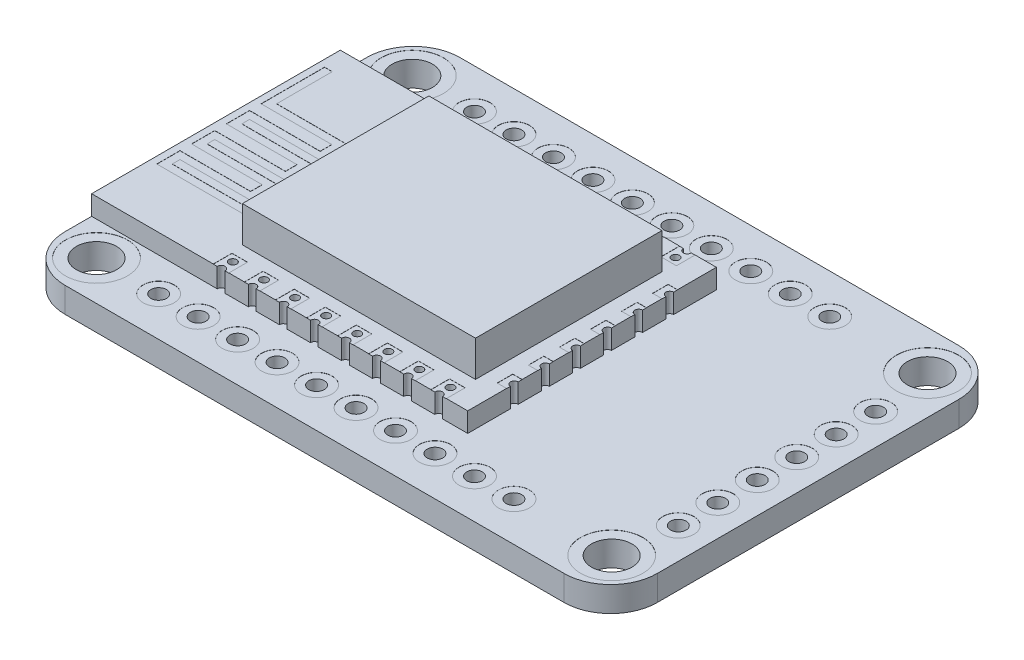
SolidWorks part; units mm, degrees
ref_plane "Front Plane" through (0, 0, 0) normal (0, 0, 1) x (1, 0, 0)
ref_plane "Top Plane" through (0, 0, 0) normal (0, 1, 0) x (1, 0, 0)
ref_plane "Right Plane" through (0, 0, 0) normal (1, 0, 0) x (0, 0, -1)
sketch "Sketch1" plane through (0, 0, 0) normal (0, 1, 0) x (1, 0, 0)
  line L1 (-19.05, -12.7) -> (19.05, -12.7)
  line L2 (-19.05, -12.7) -> (-19.05, 12.7)
  line L3 (-19.05, 12.7) -> (19.05, 12.7)
  line L4 (19.05, -12.7) -> (19.05, 12.7)
  line L5 (-19.05, -12.7) -> (19.05, 12.7) construction
  line L6 (-19.05, 12.7) -> (19.05, -12.7) construction
  point P0 (0, 0)
  dimension "D1" = 25.4
  dimension "D2" = 38.1
extrude "Boss-Extrude1" add sketch "Sketch1" along normal blind 1.62
fillet "Fillet1" radius 3 4 edges at (-19.05, 0.81, -12.7) (19.05, 0.81, -12.7) (19.05, 0.81, 12.7) (-19.05, 0.81, 12.7)
sketch "Sketch2" plane through (0, 1.62, 0) normal (0, 1, 0) x (1, 0, 0)
  line L0 (-20.6005, 0) -> (20.6768, 0) construction
  line L1 (0, 14.1473) -> (0, -15.4074) construction
  circle A0 centre (-16.575, 10.16) radius 1.3
  circle A1 centre (16.575, 10.16) radius 1.3
  circle A2 centre (16.575, -10.16) radius 1.3
  circle A3 centre (-16.575, -10.16) radius 1.3
  dimension "D1" = 2.6
  dimension "D2" = 10.16
  dimension "D3" = 16.575
extrude "Cut-Extrude1" cut sketch "Sketch2" against normal through all
sketch "Sketch4" plane through (0, 1.62, 0) normal (0, 1, 0) x (1, 0, 0)
  line L0 (-20.7466, 0) -> (20.5407, 0) construction
  line L1 (0, 13.8309) -> (0, -14.5222) construction
  circle A0 centre (16.575, 10.16) radius 2
  circle A1 centre (-16.575, 10.16) radius 2
  circle A2 centre (16.575, -10.16) radius 2
  circle A3 centre (-16.575, -10.16) radius 2
  dimension "D1" = 4
extrude "Cut-Extrude2" cut sketch "Sketch4" against normal blind 0.01
sketch "Sketch3" plane through (0, 1.62, 0) normal (0, 1, 0) x (1, 0, 0)
  line L0 (-21.1351, 0) -> (21.8987, 0) construction
  line L1 (16.575, 10.16) -> (-16.575, 10.16) construction
  line L2 (19.05, -9.7) -> (19.05, 9.7) construction
  line L3 (17.05, 6.35) -> (17.05, -6.35) construction
  circle A0 centre (-12.575, 10.16) radius 0.5
  circle A1 centre (-10.035, 10.16) radius 0.5
  circle A2 centre (-7.495, 10.16) radius 0.5
  circle A3 centre (-4.955, 10.16) radius 0.5
  circle A4 centre (-2.415, 10.16) radius 0.5
  circle A5 centre (0.125, 10.16) radius 0.5
  circle A6 centre (2.665, 10.16) radius 0.5
  circle A7 centre (5.205, 10.16) radius 0.5
  circle A8 centre (7.745, 10.16) radius 0.5
  circle A9 centre (10.285, 10.16) radius 0.5
  circle A10 centre (-16.575, 10.16) radius 1.3 construction
  circle A13 centre (10.285, -10.16) radius 0.5
  circle A14 centre (7.745, -10.16) radius 0.5
  circle A15 centre (5.205, -10.16) radius 0.5
  circle A16 centre (2.665, -10.16) radius 0.5
  circle A17 centre (0.125, -10.16) radius 0.5
  circle A18 centre (-2.415, -10.16) radius 0.5
  circle A19 centre (-4.955, -10.16) radius 0.5
  circle A20 centre (-7.495, -10.16) radius 0.5
  circle A21 centre (-10.035, -10.16) radius 0.5
  circle A22 centre (-12.575, -10.16) radius 0.5
  circle A23 centre (17.05, 6.35) radius 0.5
  circle A24 centre (17.05, 3.81) radius 0.5
  circle A25 centre (17.05, 1.27) radius 0.5
  circle A26 centre (17.05, -1.27) radius 0.5
  circle A27 centre (17.05, -3.81) radius 0.5
  circle A28 centre (17.05, -6.35) radius 0.5
  point P53 (17.05, 0)
  dimension "D1" = 1
  dimension "D5" = 2
  dimension "D3" = 2.54
  dimension "D4" = 4
  dimension "D7" = 2.54
  dimension "D2" = 10
  dimension "D6" = 6
extrude "Cut-Extrude3" cut sketch "Sketch3" against normal through all
sketch "Sketch6" plane through (0, 1.62, 0) normal (0, 1, 0) x (1, 0, 0)
  circle A0 centre (2.665, 10.16) radius 1
  circle A1 centre (2.665, 10.16) radius 0.5
  circle A2 centre (2.665, 10.16) radius 0.5 construction
  circle A3 centre (0.125, 10.16) radius 0.5
  circle A4 centre (0.125, 10.16) radius 0.5 construction
  circle A5 centre (-2.415, 10.16) radius 0.5
  circle A6 centre (-2.415, 10.16) radius 0.5 construction
  circle A7 centre (-4.955, 10.16) radius 0.5
  circle A8 centre (-4.955, 10.16) radius 0.5 construction
  circle A9 centre (-7.495, 10.16) radius 0.5
  circle A10 centre (-7.495, 10.16) radius 0.5 construction
  circle A11 centre (-10.035, 10.16) radius 0.5
  circle A12 centre (-10.035, 10.16) radius 0.5 construction
  circle A13 centre (-12.575, 10.16) radius 0.5
  circle A14 centre (-12.575, 10.16) radius 0.5 construction
  circle A15 centre (5.205, -10.16) radius 0.5
  circle A16 centre (5.205, -10.16) radius 0.5 construction
  circle A17 centre (7.745, -10.16) radius 0.5
  circle A18 centre (7.745, -10.16) radius 0.5 construction
  circle A19 centre (10.285, -10.16) radius 0.5
  circle A20 centre (10.285, -10.16) radius 0.5 construction
  circle A21 centre (10.285, 10.16) radius 0.5
  circle A22 centre (10.285, 10.16) radius 0.5 construction
  circle A23 centre (7.745, 10.16) radius 0.5
  circle A24 centre (7.745, 10.16) radius 0.5 construction
  circle A25 centre (5.205, 10.16) radius 0.5
  circle A26 centre (5.205, 10.16) radius 0.5 construction
  circle A27 centre (-12.575, -10.16) radius 0.5
  circle A28 centre (-12.575, -10.16) radius 0.5 construction
  circle A29 centre (-10.035, -10.16) radius 0.5
  circle A30 centre (-10.035, -10.16) radius 0.5 construction
  circle A31 centre (-7.495, -10.16) radius 0.5
  circle A32 centre (-7.495, -10.16) radius 0.5 construction
  circle A33 centre (-4.955, -10.16) radius 0.5
  circle A34 centre (-4.955, -10.16) radius 0.5 construction
  circle A35 centre (-2.415, -10.16) radius 0.5
  circle A36 centre (-2.415, -10.16) radius 0.5 construction
  circle A37 centre (0.125, -10.16) radius 0.5
  circle A38 centre (0.125, -10.16) radius 0.5 construction
  circle A39 centre (2.665, -10.16) radius 0.5
  circle A40 centre (2.665, -10.16) radius 0.5 construction
  circle A41 centre (17.05, -3.81) radius 0.5
  circle A42 centre (17.05, -3.81) radius 0.5 construction
  circle A43 centre (17.05, -1.27) radius 0.5
  circle A44 centre (17.05, -1.27) radius 0.5 construction
  circle A45 centre (17.05, 1.27) radius 0.5
  circle A46 centre (17.05, 1.27) radius 0.5 construction
  circle A47 centre (17.05, 3.81) radius 0.5
  circle A48 centre (17.05, 3.81) radius 0.5 construction
  circle A49 centre (17.05, 6.35) radius 0.5
  circle A50 centre (17.05, 6.35) radius 0.5 construction
  circle A51 centre (17.05, -6.35) radius 0.5
  circle A52 centre (17.05, -6.35) radius 0.5 construction
  circle A53 centre (0.125, 10.16) radius 1
  circle A54 centre (-2.415, 10.16) radius 1
  circle A55 centre (-4.955, 10.16) radius 1
  circle A56 centre (-7.495, 10.16) radius 1
  circle A57 centre (-10.035, 10.16) radius 1
  circle A58 centre (-12.575, 10.16) radius 1
  circle A59 centre (5.205, -10.16) radius 1
  circle A60 centre (7.745, -10.16) radius 1
  circle A61 centre (10.285, -10.16) radius 1
  circle A62 centre (10.285, 10.16) radius 1
  circle A63 centre (7.745, 10.16) radius 1
  circle A64 centre (5.205, 10.16) radius 1
  circle A65 centre (-12.575, -10.16) radius 1
  circle A66 centre (-10.035, -10.16) radius 1
  circle A67 centre (-7.495, -10.16) radius 1
  circle A68 centre (-4.955, -10.16) radius 1
  circle A69 centre (-2.415, -10.16) radius 1
  circle A70 centre (0.125, -10.16) radius 1
  circle A71 centre (2.665, -10.16) radius 1
  circle A72 centre (17.05, -3.81) radius 1
  circle A73 centre (17.05, -1.27) radius 1
  circle A74 centre (17.05, 1.27) radius 1
  circle A75 centre (17.05, 3.81) radius 1
  circle A76 centre (17.05, 6.35) radius 1
  circle A77 centre (17.05, -6.35) radius 1
  dimension "D1" = 0
  dimension "D2" = 0
  dimension "D3" = 0
  dimension "D4" = 0
  dimension "D5" = 0
  dimension "D6" = 0
  dimension "D7" = 0
  dimension "D8" = 0
  dimension "D9" = 0
  dimension "D10" = 0
  dimension "D11" = 0
  dimension "D12" = 0
  dimension "D13" = 0
  dimension "D14" = 0
  dimension "D15" = 0
  dimension "D16" = 0
  dimension "D17" = 0
  dimension "D18" = 0
  dimension "D19" = 0
  dimension "D20" = 0
  dimension "D21" = 0
  dimension "D22" = 0
  dimension "D23" = 0
  dimension "D24" = 0
  dimension "D25" = 0
  dimension "D26" = 0
  dimension "D27" = 0.5
extrude "Cut-Extrude4" cut sketch "Sketch6" against normal blind 0.01
sketch "Sketch7" plane through (0, 1.62, 0) normal (0, 1, 0) x (1, 0, 0)
  line L0 (-19.05, 9.7) -> (-19.05, -9.7) construction
  line L1 (-19.05, 8) -> (5.15, 8)
  line L2 (-19.05, 8) -> (-19.05, -8)
  line L3 (-19.05, -8) -> (5.15, -8)
  line L4 (5.15, 8) -> (5.15, -8)
  point P6 (-19.05, 0)
  dimension "D1" = 16
  dimension "D2" = 24.2
extrude "Boss-Extrude2" add sketch "Sketch7" along normal blind 1.26
sketch "Sketch8" plane through (0, 2.88, 0) normal (0, 1, 0) x (1, 0, 0)
  line L0 (-19.05, 8) -> (-19.05, -8) construction
  line L1 (-11.35, 6) -> (3.65, 6)
  line L2 (-11.35, 6) -> (-11.35, -6)
  line L3 (-11.35, -6) -> (3.65, -6)
  line L4 (3.65, 6) -> (3.65, -6)
  point P4 (-11.35, 0)
  dimension "D1" = 15
  dimension "D2" = 12
  dimension "D3" = 7.7
extrude "Boss-Extrude3" add sketch "Sketch8" along normal blind 2.3
sketch "Sketch9" plane through (0, 2.88, 0) normal (0, 1, 0) x (1, 0, 0)
  line L0 (-21.5126, 0) -> (22.1016, 0) construction
  line L1 (-19.05, 8) -> (-19.05, -8) construction
  line L2 (5.15, 8) -> (-19.05, 8) construction
  line L3 (5.15, -8) -> (5.15, 8) construction
  line L4 (5.15, 5) -> (5.15, -5) construction
  circle A0 centre (-10.7186, 7.2412) radius 0.25
  circle A1 centre (-8.7186, 7.2412) radius 0.25
  circle A2 centre (-6.7186, 7.2412) radius 0.25
  circle A3 centre (-4.7186, 7.2412) radius 0.25
  circle A4 centre (-2.7186, 7.2412) radius 0.25
  circle A5 centre (-0.7186, 7.2412) radius 0.25
  circle A6 centre (1.2814, 7.2412) radius 0.25
  circle A7 centre (3.2814, 7.2412) radius 0.25
  circle A8 centre (-8.7186, 7.9912) radius 0.25
  circle A9 centre (-6.7186, 7.9912) radius 0.25
  circle A10 centre (-4.7186, 7.9912) radius 0.25
  circle A11 centre (-2.7186, 7.9912) radius 0.25
  circle A12 centre (-0.7186, 7.9912) radius 0.25
  circle A13 centre (1.2814, 7.9912) radius 0.25
  circle A14 centre (3.2814, 7.9912) radius 0.25
  circle A15 centre (-10.7186, 7.9912) radius 0.25
  circle A16 centre (-10.7186, -7.9912) radius 0.25
  circle A17 centre (3.2814, -7.9912) radius 0.25
  circle A18 centre (1.2814, -7.9912) radius 0.25
  circle A19 centre (-0.7186, -7.9912) radius 0.25
  circle A20 centre (-2.7186, -7.9912) radius 0.25
  circle A21 centre (-4.7186, -7.9912) radius 0.25
  circle A22 centre (-6.7186, -7.9912) radius 0.25
  circle A23 centre (-8.7186, -7.9912) radius 0.25
  circle A24 centre (3.2814, -7.2412) radius 0.25
  circle A25 centre (1.2814, -7.2412) radius 0.25
  circle A26 centre (-0.7186, -7.2412) radius 0.25
  circle A27 centre (-2.7186, -7.2412) radius 0.25
  circle A28 centre (-4.7186, -7.2412) radius 0.25
  circle A29 centre (-6.7186, -7.2412) radius 0.25
  circle A30 centre (-8.7186, -7.2412) radius 0.25
  circle A31 centre (-10.7186, -7.2412) radius 0.25
  circle A32 centre (5.15, 5) radius 0.25
  circle A33 centre (5.15, 3) radius 0.25
  circle A34 centre (5.15, 1) radius 0.25
  circle A35 centre (5.15, -1) radius 0.25
  circle A36 centre (5.15, -3) radius 0.25
  circle A37 centre (5.15, -5) radius 0.25
  point P75 (5.15, 0)
  dimension "D1" = 0.5
  dimension "D8" = 0.5
  dimension "D4" = 0.75
  dimension "D5" = 2
  dimension "D6" = 8.3314
  dimension "D7" = 0.7588
  dimension "D10" = 2
  dimension "D2" = 8
  dimension "D3" = 2
  dimension "D9" = 6
extrude "Cut-Extrude5" cut sketch "Sketch9" against normal up to surface (1.26 mm away) up to face at (16.575, 1.62, -8.16)
sketch "Sketch10" plane through (0, 2.88, 0) normal (0, 1, 0) x (1, 0, 0)
  line L0 (-10.9685, 8) -> (-19.05, 8) construction
  line L1 (-11.2186, 8) -> (-10.2186, 8)
  line L2 (-11.2186, 8) -> (-11.2186, 6.8)
  line L3 (-11.2186, 6.8) -> (-10.2186, 6.8)
  line L4 (-10.2186, 8) -> (-10.2186, 6.8)
  line L5 (-19.6707, 0) -> (20.0452, 0) construction
  line L6 (-9.2186, 8) -> (-8.2186, 8)
  line L7 (-9.2186, 8) -> (-9.2186, 6.8)
  line L8 (-9.2186, 6.8) -> (-8.2186, 6.8)
  line L9 (-8.2186, 8) -> (-8.2186, 6.8)
  line L10 (-7.2186, 8) -> (-6.2186, 8)
  line L11 (-7.2186, 8) -> (-7.2186, 6.8)
  line L12 (-7.2186, 6.8) -> (-6.2186, 6.8)
  line L13 (-6.2186, 8) -> (-6.2186, 6.8)
  line L14 (-5.2186, 8) -> (-4.2186, 8)
  line L15 (-5.2186, 8) -> (-5.2186, 6.8)
  line L16 (-5.2186, 6.8) -> (-4.2186, 6.8)
  line L17 (-4.2186, 8) -> (-4.2186, 6.8)
  line L18 (-3.2186, 8) -> (-2.2186, 8)
  line L19 (-3.2186, 8) -> (-3.2186, 6.8)
  line L20 (-3.2186, 6.8) -> (-2.2186, 6.8)
  line L21 (-2.2186, 8) -> (-2.2186, 6.8)
  line L22 (-1.2186, 8) -> (-0.2186, 8)
  line L23 (-1.2186, 8) -> (-1.2186, 6.8)
  line L24 (-1.2186, 6.8) -> (-0.2186, 6.8)
  line L25 (-0.2186, 8) -> (-0.2186, 6.8)
  line L26 (0.7814, 8) -> (1.7814, 8)
  line L27 (0.7814, 8) -> (0.7814, 6.8)
  line L28 (0.7814, 6.8) -> (1.7814, 6.8)
  line L29 (1.7814, 8) -> (1.7814, 6.8)
  line L30 (2.7814, 8) -> (3.7814, 8)
  line L31 (2.7814, 8) -> (2.7814, 6.8)
  line L32 (2.7814, 6.8) -> (3.7814, 6.8)
  line L33 (3.7814, 8) -> (3.7814, 6.8)
  line L34 (3.7814, -8) -> (3.7814, -6.8)
  line L35 (2.7814, -6.8) -> (3.7814, -6.8)
  line L36 (2.7814, -8) -> (2.7814, -6.8)
  line L37 (2.7814, -8) -> (3.7814, -8)
  line L38 (1.7814, -8) -> (1.7814, -6.8)
  line L39 (0.7814, -6.8) -> (1.7814, -6.8)
  line L40 (0.7814, -8) -> (0.7814, -6.8)
  line L41 (0.7814, -8) -> (1.7814, -8)
  line L42 (-0.2186, -8) -> (-0.2186, -6.8)
  line L43 (-1.2186, -6.8) -> (-0.2186, -6.8)
  line L44 (-1.2186, -8) -> (-1.2186, -6.8)
  line L45 (-1.2186, -8) -> (-0.2186, -8)
  line L46 (-2.2186, -8) -> (-2.2186, -6.8)
  line L47 (-3.2186, -6.8) -> (-2.2186, -6.8)
  line L48 (-3.2186, -8) -> (-3.2186, -6.8)
  line L49 (-3.2186, -8) -> (-2.2186, -8)
  line L50 (-4.2186, -8) -> (-4.2186, -6.8)
  line L51 (-5.2186, -6.8) -> (-4.2186, -6.8)
  line L52 (-5.2186, -8) -> (-5.2186, -6.8)
  line L53 (-5.2186, -8) -> (-4.2186, -8)
  line L54 (-6.2186, -8) -> (-6.2186, -6.8)
  line L55 (-7.2186, -6.8) -> (-6.2186, -6.8)
  line L56 (-7.2186, -8) -> (-7.2186, -6.8)
  line L57 (-7.2186, -8) -> (-6.2186, -8)
  line L58 (-8.2186, -8) -> (-8.2186, -6.8)
  line L59 (-9.2186, -6.8) -> (-8.2186, -6.8)
  line L60 (-9.2186, -8) -> (-9.2186, -6.8)
  line L61 (-9.2186, -8) -> (-8.2186, -8)
  line L62 (-10.2186, -8) -> (-10.2186, -6.8)
  line L63 (-11.2186, -6.8) -> (-10.2186, -6.8)
  line L64 (-11.2186, -8) -> (-11.2186, -6.8)
  line L65 (-11.2186, -8) -> (-10.2186, -8)
  line L66 (5.15, 5.25) -> (5.15, 8) construction
  line L67 (5.15, 5.5) -> (4.55, 5.5)
  line L68 (5.15, 5.5) -> (5.15, 4.5)
  line L69 (5.15, 4.5) -> (4.55, 4.5)
  line L70 (4.55, 5.5) -> (4.55, 4.5)
  line L71 (5.15, 3.5) -> (4.55, 3.5)
  line L72 (5.15, 3.5) -> (5.15, 2.5)
  line L73 (5.15, 2.5) -> (4.55, 2.5)
  line L74 (4.55, 3.5) -> (4.55, 2.5)
  line L75 (5.15, 1.5) -> (4.55, 1.5)
  line L76 (5.15, 1.5) -> (5.15, 0.5)
  line L77 (5.15, 0.5) -> (4.55, 0.5)
  line L78 (4.55, 1.5) -> (4.55, 0.5)
  line L79 (5.15, -0.5) -> (4.55, -0.5)
  line L80 (5.15, -0.5) -> (5.15, -1.5)
  line L81 (5.15, -1.5) -> (4.55, -1.5)
  line L82 (4.55, -0.5) -> (4.55, -1.5)
  line L83 (5.15, -2.5) -> (4.55, -2.5)
  line L84 (5.15, -2.5) -> (5.15, -3.5)
  line L85 (5.15, -3.5) -> (4.55, -3.5)
  line L86 (4.55, -2.5) -> (4.55, -3.5)
  line L87 (5.15, -4.5) -> (4.55, -4.5)
  line L88 (5.15, -4.5) -> (5.15, -5.5)
  line L89 (5.15, -5.5) -> (4.55, -5.5)
  line L90 (4.55, -4.5) -> (4.55, -5.5)
  line L91 (-18.6082, 6.5485) -> (-18.6082, 2.4658)
  line L92 (-18.6082, 2.4658) -> (-14.065, 2.4658)
  line L93 (-14.065, 2.4658) -> (-14.065, 1.7212)
  line L94 (-14.065, 1.7212) -> (-18.6082, 1.7212)
  line L95 (-18.6082, 1.7212) -> (-18.6082, 0.2282)
  line L96 (-18.6082, 0.2282) -> (-14.065, 0.2282)
  line L97 (-14.065, 0.2282) -> (-14.065, -0.5165)
  line L98 (-14.065, -0.5165) -> (-18.6082, -0.5165)
  line L99 (-18.6082, -0.5165) -> (-18.6082, -2.0095)
  line L100 (-18.6082, -2.0095) -> (-14.065, -2.0095)
  line L101 (-14.065, -2.0095) -> (-14.065, -2.7541)
  line L102 (-14.065, -2.7541) -> (-18.6082, -2.7541)
  line L103 (-18.6082, -2.7541) -> (-18.6082, -4.2472)
  line L104 (-18.6082, -4.2472) -> (-11.8485, -4.2472)
  line L105 (-11.8485, -4.2472) -> (-11.8485, 2.4658)
  line L106 (-18.1082, 6.5485) -> (-18.1082, 2.9658)
  line L107 (-18.1082, 2.9658) -> (-13.565, 2.9658)
  line L108 (-13.565, 2.9658) -> (-13.565, 1.2212)
  line L109 (-13.565, 1.2212) -> (-18.1082, 1.2212)
  line L110 (-18.1082, 1.2212) -> (-18.1082, 0.7282)
  line L111 (-18.1082, 0.7282) -> (-13.565, 0.7282)
  line L112 (-13.565, 0.7282) -> (-13.565, -1.0165)
  line L113 (-13.565, -1.0165) -> (-18.1082, -1.0165)
  line L114 (-18.1082, -1.0165) -> (-18.1082, -1.5095)
  line L115 (-18.1082, -1.5095) -> (-13.565, -1.5095)
  line L116 (-13.565, -1.5095) -> (-13.565, -3.2541)
  line L117 (-13.565, -3.2541) -> (-18.1082, -3.2541)
  line L118 (-18.1082, -3.2541) -> (-18.1082, -3.7472)
  line L119 (-18.1082, -3.7472) -> (-12.3485, -3.7472)
  line L120 (-12.3485, -3.7472) -> (-12.3485, 2.4658)
  line L121 (-18.1082, 6.5485) -> (-18.6082, 6.5485)
  line L122 (-11.8485, 2.4658) -> (-12.3485, 2.4658)
  point P6 (-10.7186, 7.2412)
  point P8 (-10.7186, 6.8)
  point P17 (-8.7186, 7.2412)
  point P22 (-6.7186, 7.2412)
  point P27 (-4.7186, 7.2412)
  point P32 (-2.7186, 7.2412)
  point P37 (-0.7186, 7.2412)
  point P42 (1.2814, 7.2412)
  point P47 (3.2814, 7.2412)
  point P79 (3.2814, -7.2412)
  point P80 (1.2814, -7.2412)
  point P81 (-0.7186, -7.2412)
  point P82 (-2.7186, -7.2412)
  point P83 (-4.7186, -7.2412)
  point P84 (-6.7186, -7.2412)
  point P85 (-8.7186, -7.2412)
  point P86 (-10.7186, -7.2412)
  point P93 (5.15, 5)
  point P94 (4.55, 5)
  point P102 (5.15, 3)
  point P107 (5.15, 1)
  point P112 (5.15, -1)
  point P117 (5.15, -3)
  point P122 (5.15, -5)
  dimension "D1" = 1
  dimension "D2" = 1.2
  dimension "D4" = 1
  dimension "D5" = 0.6
  dimension "D7" = 0.5
  dimension "D3" = 8
  dimension "D6" = 6
extrude "Cut-Extrude6" cut sketch "Sketch10" against normal blind 0.01
